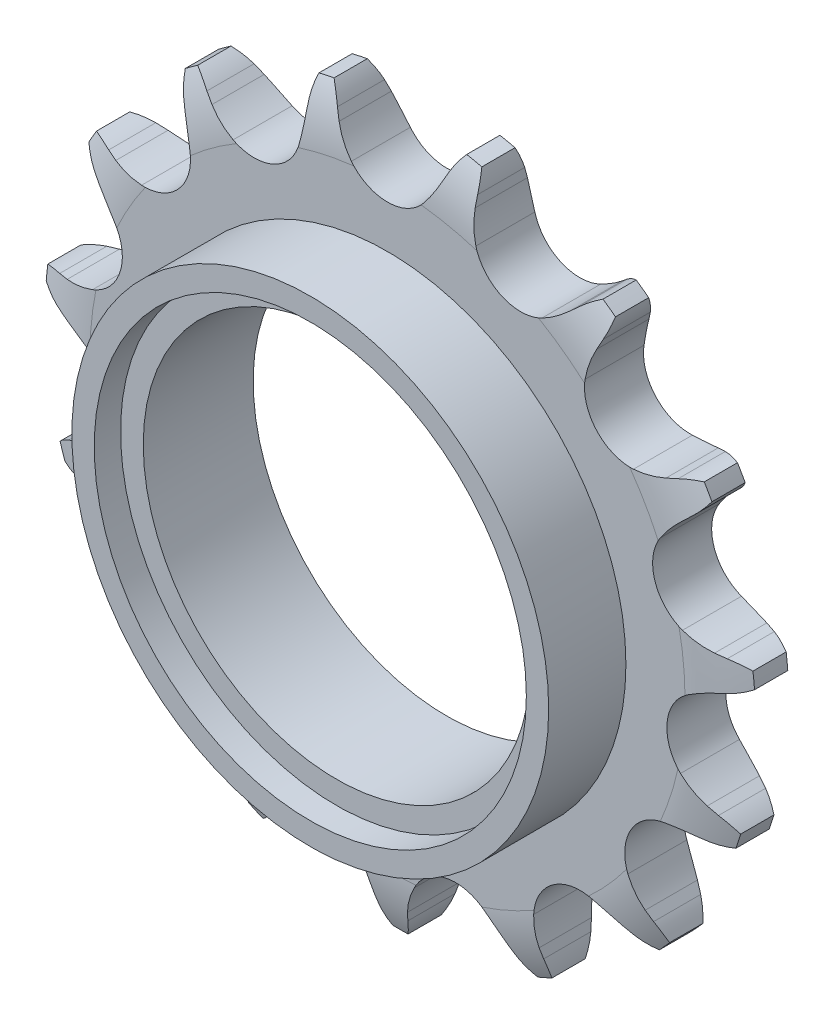
SolidWorks part; units mm, degrees
ref_plane "Front Plane" through (0, 0, 0) normal (0, 0, 1) x (1, 0, 0)
ref_plane "Top Plane" through (0, 0, 0) normal (0, 1, 0) x (1, 0, 0)
ref_plane "Right Plane" through (0, 0, 0) normal (1, 0, 0) x (0, 0, -1)
sketch "Sketch0" plane through (0, 0, 0) normal (0, 0, 1) x (1, 0, 0)
  line L0 (3, -14.1139) -> (0, 0) construction
  line L1 (0, 0) -> (8.4813, -11.6735) construction
  line L2 (0, 0) -> (-3, -14.1139) construction
  line L3 (3, -14.1139) -> (8.4813, -11.6735) construction
  line L4 (3, -14.1139) -> (-3, -14.1139) construction
  line L5 (5.4587, -13.8191) -> (5.1921, -13.4619)
  line L6 (3, -14.1139) -> (0, -14.7516) construction
  line L7 (0.6339, -14.8447) -> (0.7322, -14.4099)
  line L8 (0, -14.1139) -> (0, -15.9139) construction
  line L9 (4.2889, -12.5222) -> (0.9862, -16.6008) construction
  line L10 (0, 0) -> (0, -14.1139) construction
  line L11 (5.1921, -13.4619) -> (0.9862, -16.6008) construction
  line L12 (0, -15.9139) -> (0, -16.1712) construction
  line L13 (8.1159, -11.8362) -> (5.4587, -13.8191) construction
  circle A0 centre (0, 0) radius 15.9139 construction
  circle A1 centre (0, 0) radius 14.4292 construction
  arc A2 (-3.2007, -17.3745) -> (9.9908, -14.5706) centre (0, 0) ccw
  circle A3 centre (0, 0) radius 16.1712 construction
  circle A4 centre (3, -14.1139) radius 2 construction
  arc A7 (4.2889, -12.5222) -> (1.1751, -13.1841) centre (3, -14.1139) ccw
  circle A8 centre (3, -14.1139) radius 2.0481 construction
  arc A9 (5.4587, -13.8191) -> (9.9908, -14.5706) centre (8.1159, -11.8362) ccw
  arc A10 (5.1921, -13.4619) -> (4.2889, -12.5222) centre (0.9862, -16.6008) ccw
  arc A11 (0.6339, -14.8447) -> (-3.2007, -17.3745) centre (-2.6, -14.1139) cw
  arc A12 (0.7322, -14.4099) -> (1.1751, -13.1841) centre (5.8512, -15.5667) cw
  dimension "D1" = 2.0481
  dimension "R" = 2.0481
sketch "Sketch1" plane through (0, 0, 0) normal (1, 0, 0) x (0, 0, -1)
  line L0 (1.3, 0) -> (-1.3, 0)
  line L1 (-1.3, 0) -> (-1.3, 13.1014)
  line L2 (-1.3, 14.4292) -> (0, 14.4292) construction
  line L3 (-0.6, 15.9139) -> (0.6, 15.9139)
  line L5 (1.3, 13.1014) -> (1.3, 0)
  line L7 (0, 15.9139) -> (0, 0) construction
  line L8 (-1.3, 13.1014) -> (1.3, 13.1014) construction
  line L9 (0, 15.9139) -> (0, -15.9139) construction
  line L10 (-1.3, 13.1014) -> (-1.3, 15.9139) construction
  line L11 (-1.3, 15.9139) -> (-0.6, 15.9139) construction
  line L12 (0.6, 15.9139) -> (1.3, 15.9139) construction
  line L13 (1.3, 15.9139) -> (1.3, 13.1014) construction
  line L14 (0, 0) -> (-6.4008, 0) construction
  line L15 (-1.3, 14.4292) -> (-1.3, 10.3292) construction
  line L22 (1.3, 0) -> (-8.7, 0) construction
  line L24 (-1.3, 0) -> (-1.3, 10.3292) construction
  arc A0 (-0.6, 15.9139) -> (-1.3, 13.1014) centre (4.7, 13.1014) ccw
  arc A1 (0.6, 15.9139) -> (1.3, 13.1014) centre (-4.7, 13.1014) cw
  dimension "R" = 6
revolve "Revolve1" add sketch "Sketch1" angle 360 mid plane about L0
extrude "Cut-Extrude1" cut sketch "Sketch0" against normal through all and the other way through all
pattern_circular "CirPattern1" count 15 over 360 about axis through (0, 0, 0) along (0, 0, 1) of "Cut-Extrude1"
sketch "Sketch2" plane through (0, 0, 0) normal (0, 0, 1) x (1, 0, 0)
  circle A0 centre (0, 0) radius 3 construction
  circle A1 centre (0, 0) radius 10
  circle A2 centre (0, 0) radius 15.65 construction
  dimension "Bore" = 6
  dimension "Hub Dia." = 20
  dimension "OD" = 31.3
extrude "Boss-Extrude1" add sketch "Sketch2" along normal up to vertex (8.7 mm away) from surface at 1.3 starting at face at (0, 0, 1.3)
sketch "Sketch3" plane through (0, 0, 0) normal (0, 0, 1) x (1, 0, 0)
  circle A0 centre (0, 0) radius 3 construction
  circle A1 centre (0, 0) radius 3
extrude "Cut-Extrude2" cut sketch "Sketch3" along normal through all and the other way through all
sketch "Sketch4" plane through (0, 0, 0) normal (1, 0, 0) x (0, 0, -1)
  line L0 (-8.7, 10) -> (-8.7, 9.5)
  line L1 (-1.3, 15.9139) -> (-3.25, 15.9139)
  line L2 (-1.3, 15.9139) -> (-1.3, 10.3292)
  line L3 (-1.3, 10.3292) -> (-3.25, 10.3292)
  line L4 (-3.25, 15.9139) -> (-3.25, 10.3292)
  line L9 (-8.7, 9.5) -> (-8.2, 10)
  line L10 (-8.2, 10) -> (-8.7, 10)
  dimension "C" = 0.5
  dimension "D3" = 1.95
revolve "Cut-Revolve1" cut sketch "Sketch4" angle 360 mid plane about L22
sketch "Sketch5" plane through (0, 0, 0) normal (0, 0, 1) x (1, 0, 0)
  circle A0 centre (0, 0) radius 15.65 construction
  circle A1 centre (0, 0) radius 15.65
extrude "Cut-Extrude3" cut sketch "Sketch5" against normal through all and the other way through all flip side to cut
sketch "Sketch6" plane through (0, 0, 0) normal (0, 0, 1) x (1, 0, 0)
  circle A0 centre (0, 0) radius 10
  dimension "D1" = 20
extrude "Cut-Extrude4" cut sketch "Sketch6" against normal through all both and the other way through all
sketch "Sketch7" plane through (0, 0, 1.3) normal (0, 0, 1) x (1, 0, 0)
  circle A0 centre (0, 0) radius 10.5
  circle A2 centre (0, 0) radius 8.515
  dimension "D1" = 21
  dimension "D2" = 17.03
extrude "Boss-Extrude2" add sketch "Sketch7" along normal blind 3.4 and the other way up to surface other way up to face at (0, 10, -1.3)
sketch "Sketch8" plane through (0, 0, 4.7) normal (0, 0, 1) x (1, 0, 0)
  circle A0 centre (0, 0) radius 9.515
  dimension "D1" = 19.03
extrude "Cut-Extrude5" cut sketch "Sketch8" against normal blind 1.16
equation "\"360/N@Sketch0\" = 360/\"Teeth@CirPattern1\""
equation "\"Ds@Sketch0\" = 1.005 * \"Dr@Sketch0\" + ( 0.003 * 25.4 ) "
equation "\"R@Sketch0\" = 1/2 * \"Ds@Sketch0\""
equation "\"A@Sketch0\" = 35 +  ( 60 / \"Teeth@CirPattern1\" ) "
equation "\"B@Sketch0\" = 18 -  ( 56 / \"Teeth@CirPattern1\" )"
equation "\"ac@Sketch0\" = 0.8 * \"Dr@Sketch0\""
equation "\"ab@Sketch0\" = 1.4 * \"Dr@Sketch0\""
equation "\"J@Sketch0\" = 0.3 * \"Pitch@Sketch0\""
equation "\"D3@Sketch4\" = \"t@Sketch1\" * 3 / 4"
